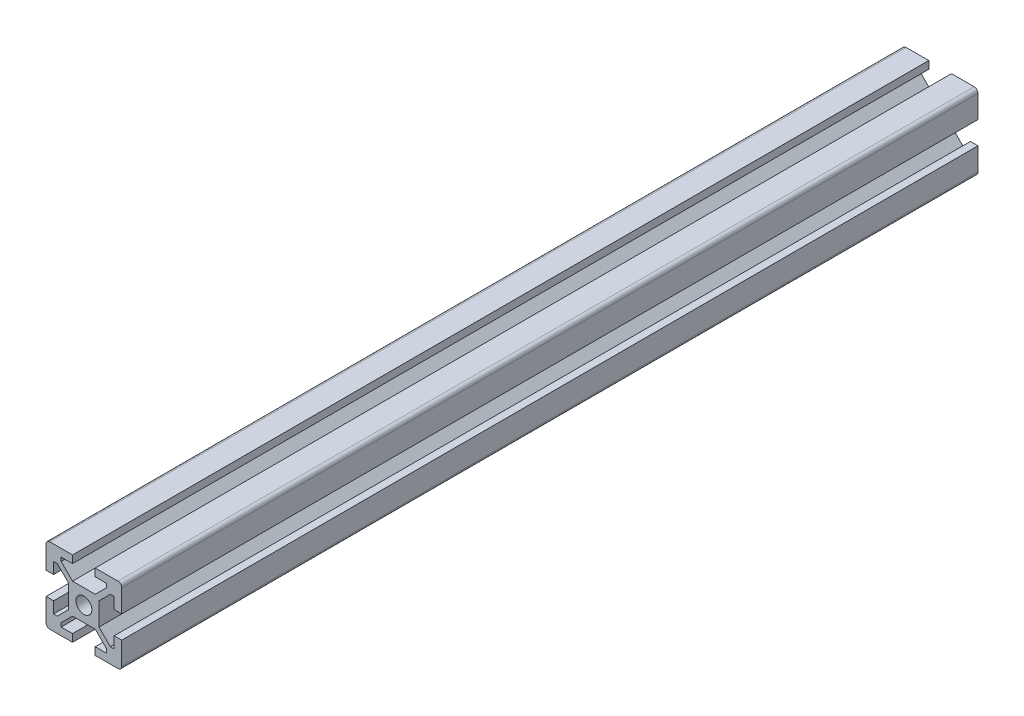
SolidWorks part; units mm, degrees
material "6063-T5"
ref_plane "Front Plane" through (0, 0, 0) normal (0, 0, 1) x (1, 0, 0)
ref_plane "Top Plane" through (0, 0, 0) normal (0, 1, 0) x (1, 0, 0)
ref_plane "Right Plane" through (0, 0, 0) normal (1, 0, 0) x (0, 0, -1)
ref_plane "Plane1" through (0, 0, 0) normal (0, 0, -1) x (-1, 0, 0)
sketch "Sketch1" plane through (0, 0, 0) normal (0, 0, -1) x (-1, 0, 0)
  line L0 (6, -8) -> (3, -8)
  line L1 (3, -8) -> (3, -10)
  line L2 (3, -10) -> (9, -10)
  line L3 (10, -9) -> (10, -3)
  line L4 (10, -3) -> (8, -3)
  line L5 (8, -3) -> (8, -6)
  line L6 (8, -6) -> (7, -6)
  line L7 (7, -6) -> (4, -3)
  line L8 (4, -3) -> (4, 3)
  line L9 (4, 3) -> (7, 6)
  line L10 (7, 6) -> (8, 6)
  line L11 (8, 6) -> (8, 3)
  line L12 (8, 3) -> (10, 3)
  line L13 (10, 3) -> (10, 9)
  line L14 (9, 10) -> (3, 10)
  line L15 (3, 10) -> (3, 8)
  line L16 (3, 8) -> (6, 8)
  line L17 (6, 8) -> (6, 7)
  line L18 (6, 7) -> (3, 4)
  line L19 (3, 4) -> (-3, 4)
  line L20 (-3, 4) -> (-6, 7)
  line L21 (-6, 7) -> (-6, 8)
  line L22 (-6, 8) -> (-3, 8)
  line L23 (-3, 8) -> (-3, 10)
  line L24 (-3, 10) -> (-9, 10)
  line L25 (-10, 9) -> (-10, 3)
  line L26 (-10, 3) -> (-8, 3)
  line L27 (-8, 3) -> (-8, 6)
  line L28 (-8, 6) -> (-7, 6)
  line L29 (-7, 6) -> (-4, 3)
  line L30 (-4, 3) -> (-4, -3)
  line L31 (-4, -3) -> (-7, -6)
  line L32 (-7, -6) -> (-8, -6)
  line L33 (-8, -6) -> (-8, -3)
  line L34 (-8, -3) -> (-10, -3)
  line L35 (-10, -3) -> (-10, -9)
  line L36 (-9, -10) -> (-3, -10)
  line L37 (-3, -10) -> (-3, -8)
  line L38 (-3, -8) -> (-6, -8)
  line L39 (-6, -8) -> (-6, -7)
  line L40 (-6, -7) -> (-3, -4)
  line L41 (-3, -4) -> (3, -4)
  line L42 (3, -4) -> (6, -7)
  line L43 (6, -7) -> (6, -8)
  line L44 (0, 4) -> (0, 0) construction
  line L45 (0, 0) -> (-4, 0) construction
  line L46 (0, 0) -> (4, 0) construction
  line L47 (0, 0) -> (0, -4) construction
  circle A0 centre (0, 0) radius 2.1
  arc A1 (9, -10) -> (10, -9) centre (9, -9) ccw
  arc A2 (10, 9) -> (9, 10) centre (9, 9) ccw
  arc A3 (-9, 10) -> (-10, 9) centre (-9, 9) ccw
  arc A4 (-10, -9) -> (-9, -10) centre (-9, -9) ccw
  dimension "D6" = 1
  dimension "D10" = 4.2
  dimension "D1" = 10
  dimension "D2" = 10
  dimension "D3" = 10
  dimension "D4" = 10
  dimension "D5" = 8
  dimension "D7" = 2
  dimension "D8" = 7
  dimension "D9" = 8
  dimension "D11" = 1
  dimension "D12" = 1
  dimension "D13" = 2
  dimension "D14" = 3
  dimension "D15" = 2
  dimension "D16" = 1
  dimension "D17" = 1
  dimension "D18" = 4.2426
  dimension "D19" = 6
  dimension "D20" = 7
extrude "Boss-Extrude1" add sketch "Sketch1" against normal blind 226.15
ref_plane "Plane2" through (0, 0, 0) normal (1, 0, 0) x (0, 0, -1)
